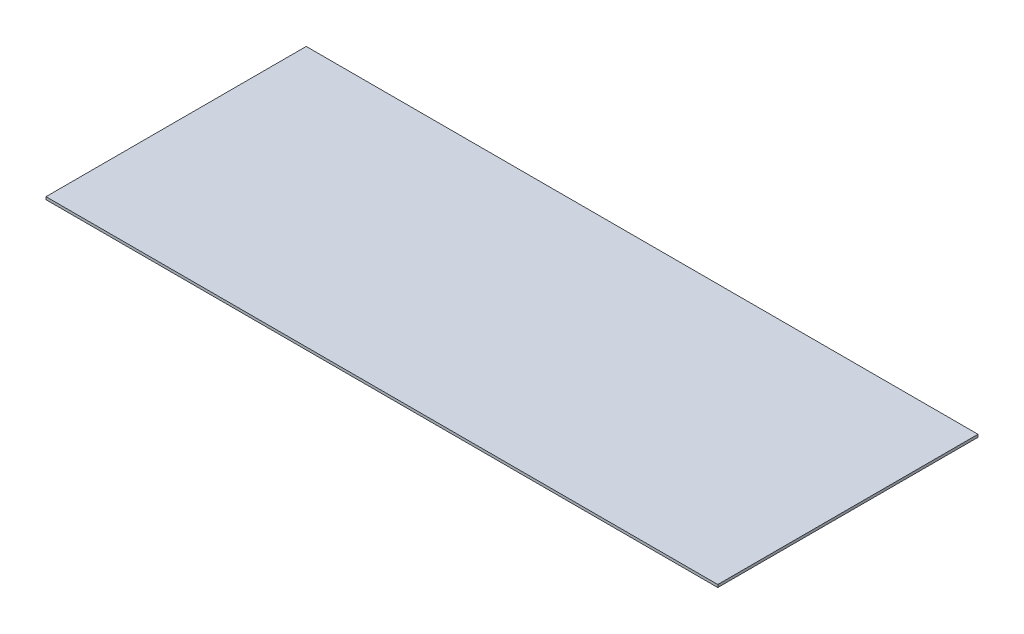
SolidWorks part; units mm, degrees
material "3003 Alloy"
ref_plane "Front Plane" through (0, 0, 0) normal (0, 0, 1) x (1, 0, 0)
ref_plane "Top Plane" through (0, 0, 0) normal (0, 1, 0) x (1, 0, 0)
ref_plane "Right Plane" through (0, 0, 0) normal (1, 0, 0) x (0, 0, -1)
sketch "Sketch1" plane through (0, 0, 0) normal (0, 0, 1) x (1, 0, 0)
  line L0 (0, 0.5969) -> (0, -0.5969)
  line L1 (-150.8125, 0) -> (150.8125, 0) construction
  point P0 (-150.8125, 0.5969)
  point P6 (0, 0)
  point P7 (-150.8125, -0.5969)
sketch "Sketch2" plane through (0, 0, 0) normal (1, 0, 0) x (0, 0, -1)
  line L0 (58.42, 0) -> (-58.42, 0)
  line L1 (58.42, -0.5969) -> (58.42, 0.5969) construction
  point P4 (0, 0)
  point P7 (58.42, 0)
  point P8 (58.42, -0.5969)
  point P9 (58.42, 0.5969)
  dimension "D1" = 1.1938
sketch "Sketch3" plane through (0, 0, 0) normal (0, 0, 1) x (1, 0, 0)
  line L1 (150.8125, 0.5969) -> (-150.8125, 0.5969)
  line L2 (150.8125, 0.5969) -> (150.8125, -0.5969)
  line L3 (150.8125, -0.5969) -> (-150.8125, -0.5969)
  line L4 (-150.8125, 0.5969) -> (-150.8125, -0.5969)
  line L5 (150.8125, 0.5969) -> (-150.8125, -0.5969) construction
  line L6 (150.8125, -0.5969) -> (-150.8125, 0.5969) construction
  point P0 (0, 0)
extrude "Boss-Extrude1" add sketch "Sketch3" along normal up to vertex (58.42 mm away) and the other way up to vertex (58.42 mm away) up to point (0, 0, 58.42) other way up to point (0, 0, -58.42)
sketch "Sketch4" plane through (0, 0, 0) normal (0, 1, 0) x (1, 0, 0)
  line L1 (150.8125, -58.42) -> (-150.8125, -58.42) construction
  line L2 (150.8125, -58.42) -> (150.8125, 58.42) construction
  line L3 (150.8125, 58.42) -> (-150.8125, 58.42) construction
  line L4 (-150.8125, -58.42) -> (-150.8125, 58.42) construction
  line L5 (150.8125, -58.42) -> (-150.8125, 58.42) construction
  line L6 (150.8125, 58.42) -> (-150.8125, -58.42) construction
  point P0 (0, 0)
  point P6 (-150.8125, 58.42)
  point P10 (150.8125, 58.42)
  point P11 (150.8125, -58.42)
equation "\"D1@Sketch2\"=\"Wire Dia@Sketch1\""
